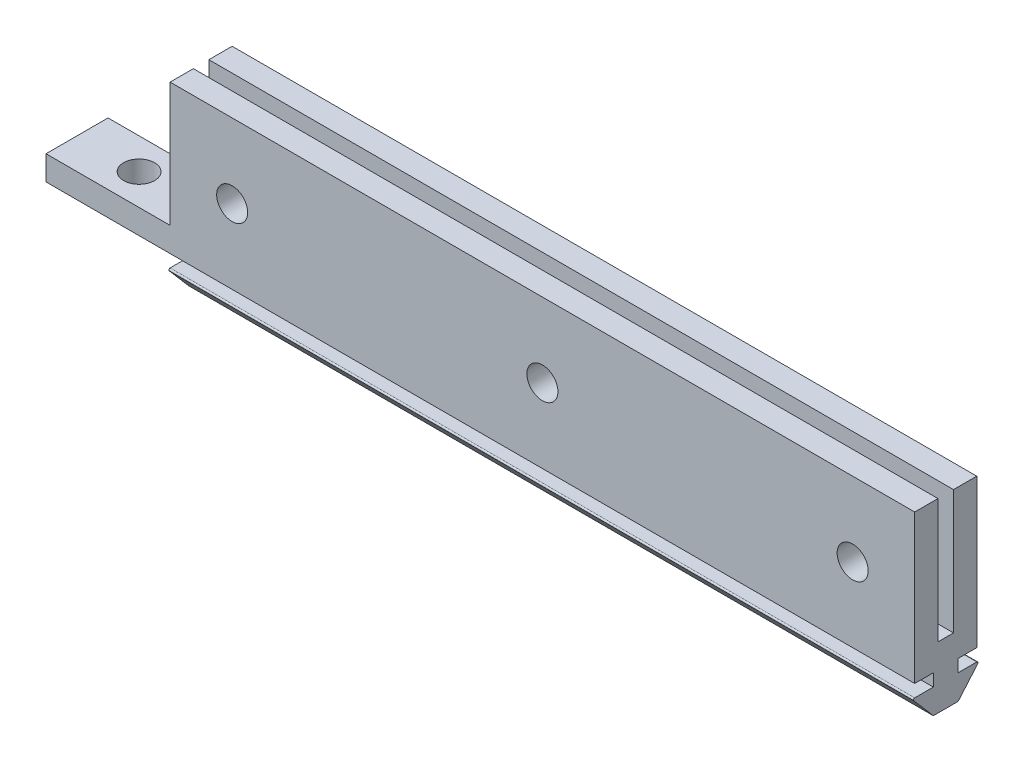
SolidWorks part; units mm, degrees
ref_plane "Front Plane" through (0, 0, 0) normal (0, 0, 1) x (1, 0, 0)
ref_plane "Top Plane" through (0, 0, 0) normal (0, 1, 0) x (1, 0, 0)
ref_plane "Right Plane" through (0, 0, 0) normal (1, 0, 0) x (0, 0, -1)
sketch "Sketch10" plane through (0, 0, 0) normal (1, 0, 0) x (0, 0, -1)
  line L2 (0, 0) -> (0, 12.7) construction
  line L4 (6.35, 10.16) -> (-6.35, 10.16)
  line L5 (-6.5427, 9.7405) -> (-2.54, 5.08)
  line L6 (6.5427, 9.7405) -> (2.54, 5.08)
  line L7 (2.54, 5.08) -> (-2.54, 5.08)
  line L16 (2.54, 12.7) -> (-2.54, 12.7)
  line L17 (-2.54, 12.7) -> (-2.54, 10.16)
  line L18 (-2.54, 10.16) -> (2.54, 10.16)
  line L19 (2.54, 10.16) -> (2.54, 12.7)
  arc A2 (6.35, 10.16) -> (6.5427, 9.7405) centre (6.35, 9.906) cw
  arc A3 (-6.35, 10.16) -> (-6.5427, 9.7405) centre (-6.35, 9.906) ccw
  point P4 (0, 5.08)
  point P10 (0, 10.16)
  point P35 (0, 12.7)
  dimension "D1" = 12.7
  dimension "D3" = 0.254
  dimension "D2" = 5.08
  dimension "D4" = 2.54
  dimension "D6" = 5.08
  dimension "D7" = 12.7
  dimension "D8" = 5.08
extrude "Boss-Extrude3" add sketch "Sketch10" against normal blind 152.4 separate body contours L7 L2 L18 L4 A3 L5 | L18 L2 L16 L17 | L2 L7 L6 A2 L4 | L2 L4 L19 L16
sketch "Sketch11" plane through (0, 0, 0) normal (1, 0, 0) x (0, 0, -1)
  line L0 (6.35, 12.7) -> (-6.35, 12.7)
  line L2 (-6.35, 12.7) -> (-6.35, 43.1)
  line L3 (-6.35, 43.1) -> (-1.5875, 43.1)
  line L4 (-1.5875, 43.1) -> (-1.5875, 17.7)
  line L5 (-1.5875, 17.7) -> (1.5875, 17.7)
  line L6 (1.5875, 17.7) -> (1.5875, 43.1)
  line L7 (1.5875, 43.1) -> (6.35, 43.1)
  line L8 (6.35, 43.1) -> (6.35, 12.7)
  line L9 (2.54, 12.7) -> (-2.54, 12.7) construction
  point P3 (0, 12.7)
  point P9 (0, 12.7)
  dimension "D1" = 3.175
  dimension "D2" = 25.4
  dimension "D3" = 5
  dimension "D4" = 12.7
extrude "Boss-Extrude4" add sketch "Sketch11" against normal offset from surface (177.8 mm away) 25.4 up to face at (-152.4, 9.5805, 0) offset beyond the face yes
sketch "Sketch14" plane through (0, 0, -6.35) normal (0, 0, -1) x (-1, 0, 0)
  line L0 (152.4, 17.7) -> (152.4, 12.7) construction
  line L5 (177.8, 43.1) -> (152.4, 43.1)
  line L6 (177.8, 43.1) -> (177.8, 17.7)
  line L7 (177.8, 17.7) -> (152.4, 17.7)
  line L8 (152.4, 43.1) -> (152.4, 17.7)
  line L9 (177.8, 17.7) -> (0, 17.7) construction
extrude "Cut-Extrude1" cut sketch "Sketch14" against normal through all
hole_wizard "1/4 (0.25) Diameter Hole1" positions "Sketch12" profile "Sketch13" hole size "1/4" standard "ANSI Inch" end condition through all
sketch "Sketch12" plane through (0, 0, -6.35) normal (0, 0, -1) x (-1, 0, 0)
  line L0 (0, 27.9) -> (152.4, 27.9) construction
  line L1 (0, 12.7) -> (0, 43.1) construction
  line L3 (152.4, 43.1) -> (152.4, 17.7) construction
  point P9 (12.7, 27.9)
  point P11 (76.2, 27.9)
  point P13 (139.7, 27.9)
  point P17 (0, 0)
  point P18 (62.23, 27.9)
  point P21 (54.0465, 27.9)
  dimension "D1" = 12.7
  dimension "D2" = 12.7
sketch "Sketch13" plane through (-139.7, 27.9, -6.35) normal (1, 0, 0) x (0, 1, 0)
  line L0 (0, 0) -> (0, 12.954)
  line L1 (0, 12.954) -> (3.175, 12.954)
  line L2 (3.175, 12.954) -> (3.175, 0)
  line L5 (3.175, 0) -> (0, 0)
  line L11 (0, -6.35) -> (0, 107.95) construction
  dimension "Thru Hole Dia." = 6.35
  dimension "Thru Hole Depth" = 12.954
hole_wizard "1/4 (0.25) Diameter Hole2" positions "Sketch15" profile "Sketch16" hole size "1/4" standard "ANSI Inch" end condition through all
sketch "Sketch15" plane through (0, 17.7, 0) normal (0, 1, 0) x (1, 0, 0)
  line L0 (-177.8, 0) -> (-165.1, 0) construction
  line L1 (-177.8, -6.35) -> (-177.8, 6.35) construction
  line L3 (-165.1, 0) -> (-165.1, 6.35) construction
  line L4 (-152.4, 6.35) -> (-177.8, 6.35) construction
  point P1 (-165.1, 0)
sketch "Sketch16" plane through (-165.1, 17.7, 0) normal (1, 0, 0) x (0, 0, 1)
  line L0 (0, 0) -> (0, 12.62)
  line L1 (0, 12.62) -> (3.175, 12.62)
  line L2 (3.175, 12.62) -> (3.175, 0)
  line L5 (3.175, 0) -> (0, 0)
  line L11 (0, -6.35) -> (0, 107.95) construction
  dimension "Thru Hole Dia." = 6.35
  dimension "Thru Hole Depth" = 12.62
